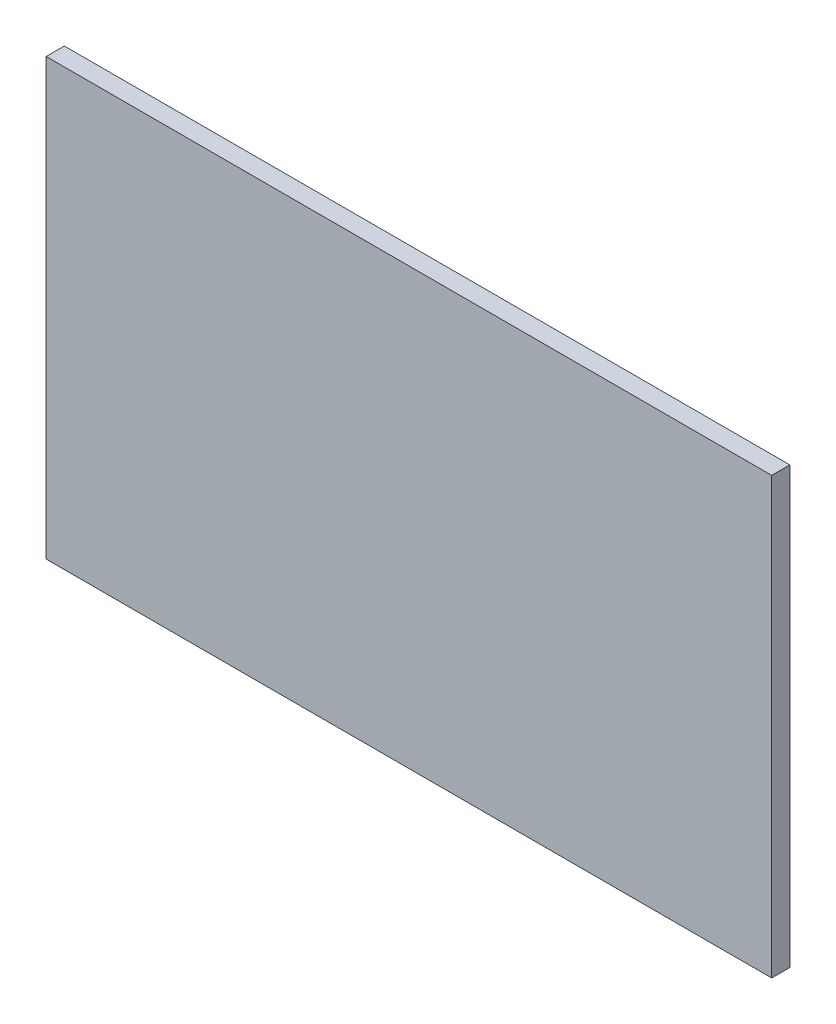
SolidWorks part; units mm, degrees
ref_plane "Front Plane" through (0, 0, 0) normal (0, 0, 1) x (1, 0, 0)
ref_plane "Top Plane" through (0, 0, 0) normal (0, 1, 0) x (1, 0, 0)
ref_plane "Right Plane" through (0, 0, 0) normal (1, 0, 0) x (0, 0, -1)
sketch "Sketch1" plane through (0, 0, 0) normal (0, 0, 1) x (1, 0, 0)
  line L1 (-254, -152.4) -> (254, -152.4)
  line L2 (-254, -152.4) -> (-254, 152.4)
  line L3 (-254, 152.4) -> (254, 152.4)
  line L4 (254, -152.4) -> (254, 152.4)
  line L5 (-254, -152.4) -> (254, 152.4) construction
  line L6 (-254, 152.4) -> (254, -152.4) construction
  point P0 (0, 0)
  dimension "D1" = 508
  dimension "D2" = 304.8
extrude "Boss-Extrude1" add sketch "Sketch1" along normal blind 12.7
